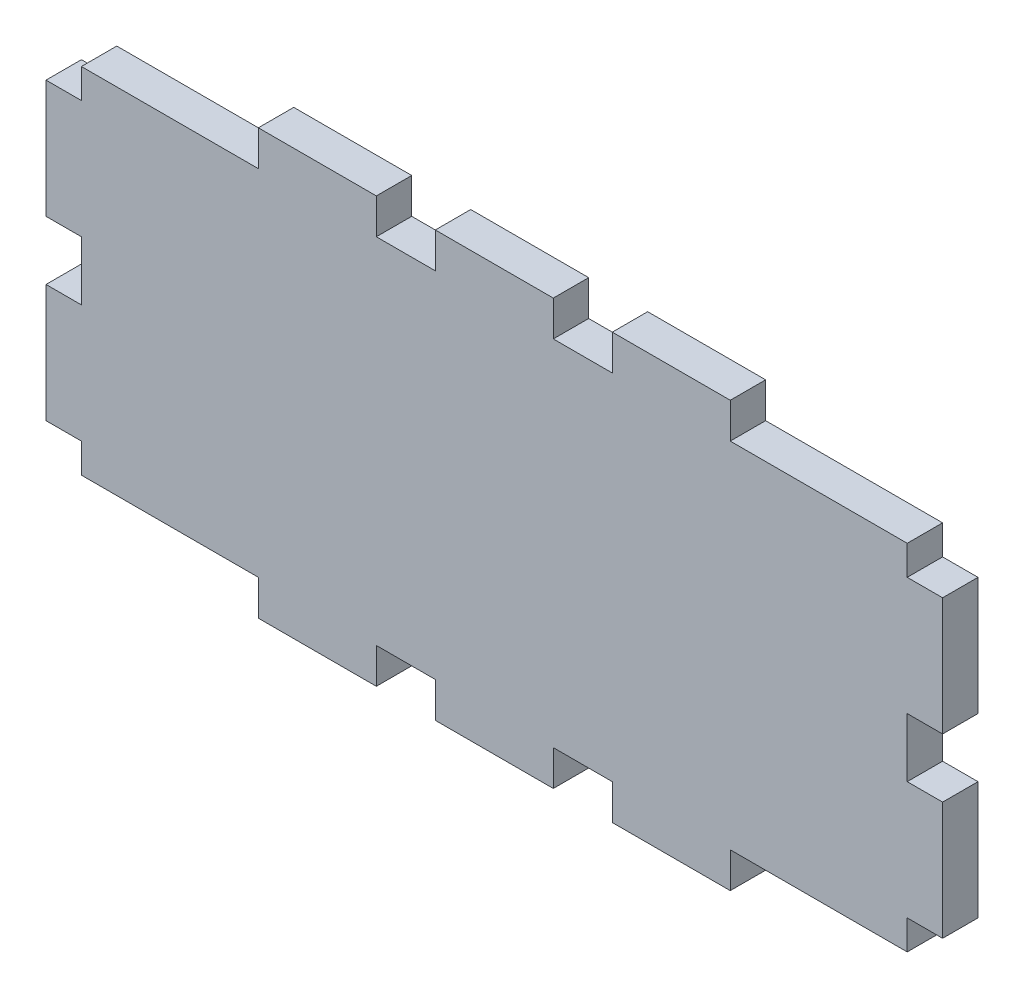
SolidWorks part; units mm, degrees
ref_plane "前视基准面" through (0, 0, 0) normal (0, 0, 1) x (1, 0, 0)
ref_plane "上视基准面" through (0, 0, 0) normal (0, 1, 0) x (1, 0, 0)
ref_plane "右视基准面" through (0, 0, 0) normal (1, 0, 0) x (0, 0, -1)
sketch "草图1" plane through (0, 0, 0) normal (0, 0, 1) x (1, 0, 0)
  line L5 (-5, 15) -> (-5, 18)
  line L6 (-35, 15) -> (-20, 15)
  line L60 (-35, 15) -> (-35, 12.5)
  line L61 (-35, -15) -> (-20, -15)
  line L83 (35, 15) -> (35, 12.5)
  line L84 (-35, 15) -> (35, -15) construction
  line L85 (-35, -15) -> (35, 15) construction
  line L87 (-20, 15) -> (-20, 18)
  line L88 (-20, 18) -> (-10, 18)
  line L89 (-10, 15) -> (-10, 18)
  line L90 (-35, 12.5) -> (-38, 12.5)
  line L92 (-35, 2.5) -> (-38, 2.5)
  line L93 (-38, 12.5) -> (-38, 2.5)
  line L95 (5, 15) -> (5, 18)
  line L96 (-5, 18) -> (5, 18)
  line L97 (10, 15) -> (10, 18)
  line L99 (20, 15) -> (20, 18)
  line L100 (10, 18) -> (20, 18)
  line L101 (55, 0) -> (-55, 0) construction
  line L103 (20, -15) -> (20, -18)
  line L104 (10, -18) -> (20, -18)
  line L105 (10, -15) -> (10, -18)
  line L107 (5, -15) -> (5, -18)
  line L108 (-5, -18) -> (5, -18)
  line L109 (-5, -15) -> (-5, -18)
  line L110 (-20, -18) -> (-10, -18)
  line L111 (-10, -15) -> (-10, -18)
  line L113 (-20, -15) -> (-20, -18)
  line L114 (-35, -2.5) -> (-38, -2.5)
  line L115 (-38, -12.5) -> (-38, -2.5)
  line L116 (-35, -12.5) -> (-38, -12.5)
  line L118 (0, -55) -> (0, 55) construction
  line L120 (35, -12.5) -> (38, -12.5)
  line L121 (38, -12.5) -> (38, -2.5)
  line L122 (35, -2.5) -> (38, -2.5)
  line L123 (35, 2.5) -> (38, 2.5)
  line L124 (38, 12.5) -> (38, 2.5)
  line L125 (35, 12.5) -> (38, 12.5)
  line L127 (-10, 15) -> (-5, 15)
  line L128 (5, 15) -> (10, 15)
  line L129 (20, 15) -> (35, 15)
  line L130 (35, 2.5) -> (35, -2.5)
  line L131 (35, -12.5) -> (35, -15)
  line L132 (20, -15) -> (35, -15)
  line L133 (5, -15) -> (10, -15)
  line L134 (-10, -15) -> (-5, -15)
  line L135 (-35, -12.5) -> (-35, -15)
  line L136 (-35, 2.5) -> (-35, -2.5)
  point P0 (0, 0)
  dimension "D1" = 70
  dimension "D2" = 30
  dimension "D3" = 10
  dimension "D4" = 3
  dimension "D5" = 15
  dimension "D7" = 3
  dimension "D8" = 2.5
  dimension "D9" = 3
  dimension "D6" = 10
extrude "凸台-拉伸1" add sketch "草图1" along normal blind 3
